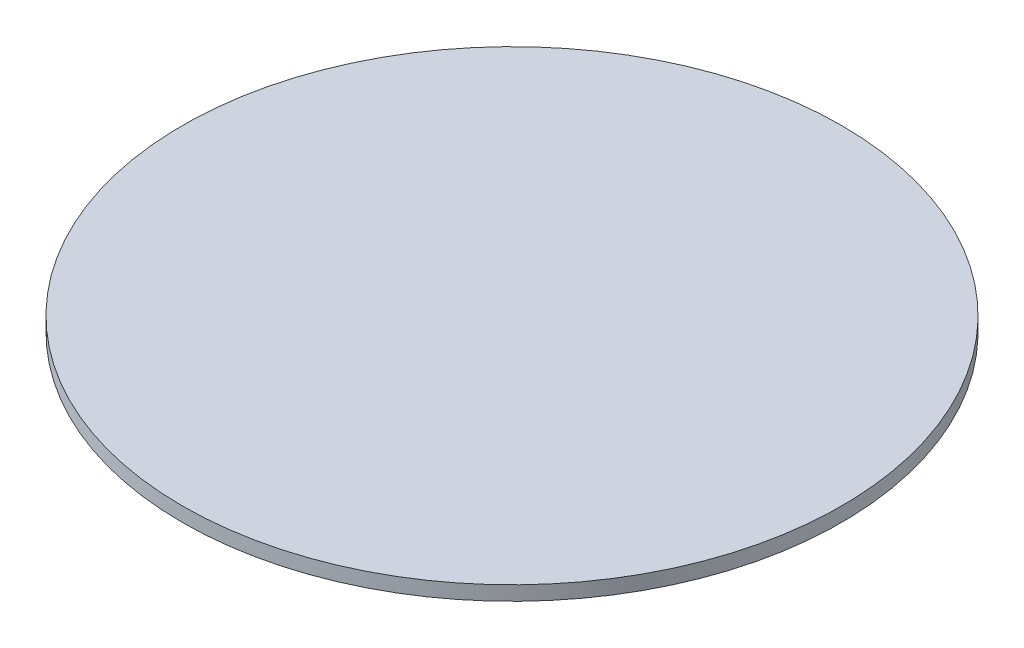
SolidWorks part; units mm, degrees
ref_plane "Front Plane" through (0, 0, 0) normal (0, 0, 1) x (1, 0, 0)
ref_plane "Top Plane" through (0, 0, 0) normal (0, 1, 0) x (1, 0, 0)
ref_plane "Right Plane" through (0, 0, 0) normal (1, 0, 0) x (0, 0, -1)
sketch "Sketch1" plane through (0, 0, 0) normal (0, 1, 0) x (1, 0, 0)
  circle A0 centre (0, 0) radius 11.5
  dimension "D1" = 23
extrude "Boss-Extrude1" add sketch "Sketch1" along normal blind 0.5
